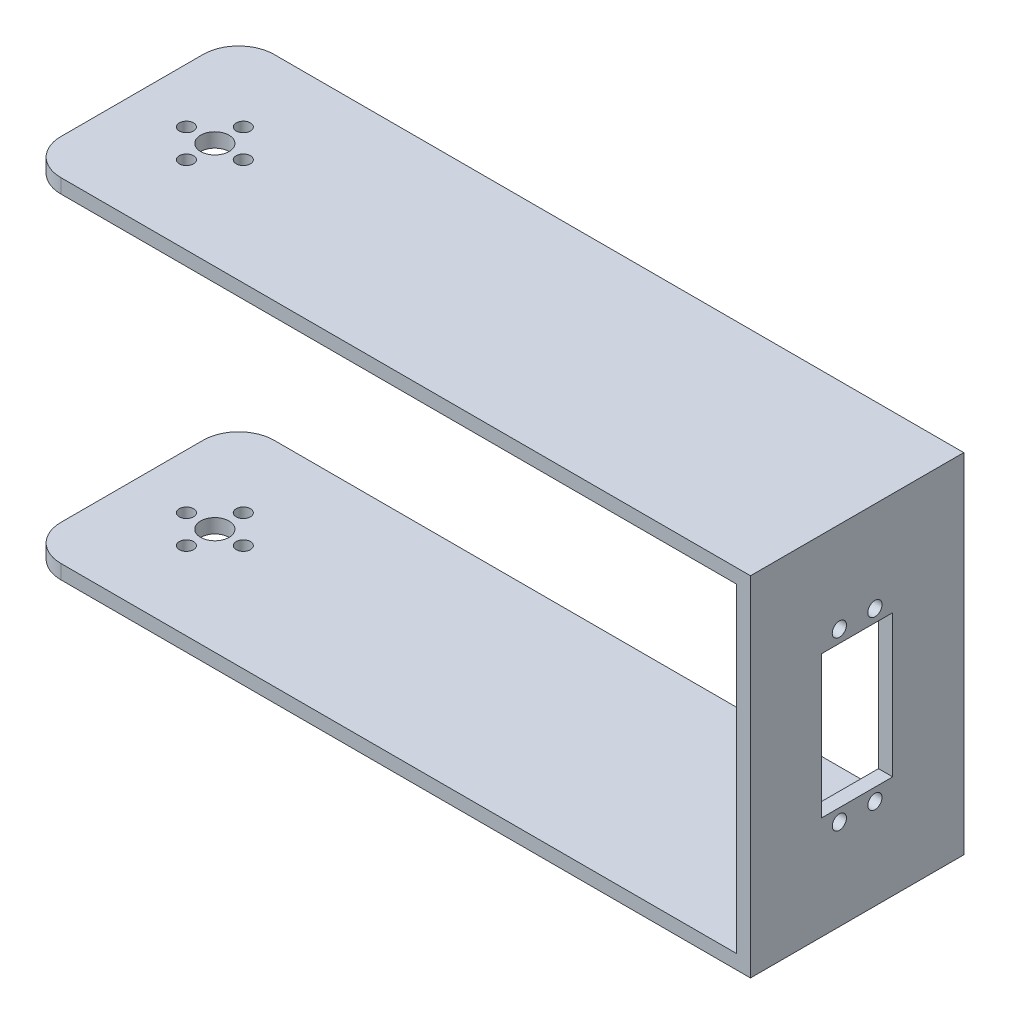
SolidWorks part; units mm, degrees
ref_plane "Ön Düzlem" through (0, 0, 0) normal (0, 0, 1) x (1, 0, 0)
ref_plane "Üst Düzlem" through (0, 0, 0) normal (0, 1, 0) x (1, 0, 0)
ref_plane "Sağ Düzlem" through (0, 0, 0) normal (1, 0, 0) x (0, 0, -1)
sketch "Çizim1" plane through (0, 0, 0) normal (0, 0, 1) x (1, 0, 0)
  line L0 (0, 0) -> (200, 0)
  line L1 (200, 0) -> (200, 90)
  line L2 (200, 90) -> (0, 90)
  dimension "D1" = 90
  dimension "D2" = 200
extrude "Ekstrüzyon-İnce1" add sketch "Çizim1" along normal blind 60 thin
fillet "Radyus1" radius 10 4 edges at (0, -2, 60) (0, -2, 0) (0, 92, 0) (0, 92, 60)
sketch "Çizim2" plane through (0, 94, 0) normal (0, 1, 0) x (1, 0, 0)
  circle A0 centre (23.3181, -30) radius 4
  circle A1 centre (23.3181, -22) radius 2
  circle A2 centre (23.3181, -38) radius 2
  circle A3 centre (31.3181, -30) radius 2
  circle A4 centre (15.3181, -30) radius 2
  dimension "D1" = 8
  dimension "D3" = 4
  dimension "D5" = 4
  dimension "D6" = 8
  dimension "D7" = 8
  dimension "D8" = 4
  dimension "D9" = 4
  dimension "D2" = 8
  dimension "D4" = 8
extrude "Kes-Ekstrüzyon1" cut sketch "Çizim2" against normal up to next
ref_plane "Düzlem1" through (0, 45, 0) normal (0, 1, 0) x (1, 0, 0)
mirror "Aynalama1" about plane through (0, 45, 0) normal (0, 1, 0) of "Kes-Ekstrüzyon1"
sketch "Çizim3" plane through (204, 0, 0) normal (1, 0, 0) x (0, 0, -1)
  line L0 (-60, -4) -> (0, -4) construction
  line L1 (-20, 25) -> (-40, 25)
  line L2 (-20, 25) -> (-20, 65)
  line L3 (-20, 65) -> (-40, 65)
  line L4 (-40, 25) -> (-40, 65)
  line L7 (0, -4) -> (0, 94) construction
  line L10 (-40, 45) -> (-20, 45) construction
  circle A0 centre (-25, 68.5) radius 2
  circle A1 centre (-35, 68.5) radius 2
  circle A2 centre (-25, 21.5) radius 2
  circle A3 centre (-35, 21.5) radius 2
  dimension "D7" = 4
  dimension "D5" = 3.5
  dimension "D6" = 10
  dimension "D9" = 5
  dimension "D8" = 3.5
  dimension "D1" = 40
  dimension "D2" = 20
  dimension "D3" = 29
  dimension "D4" = 20
extrude "Kes-Ekstrüzyon2" cut sketch "Çizim3" against normal up to next
